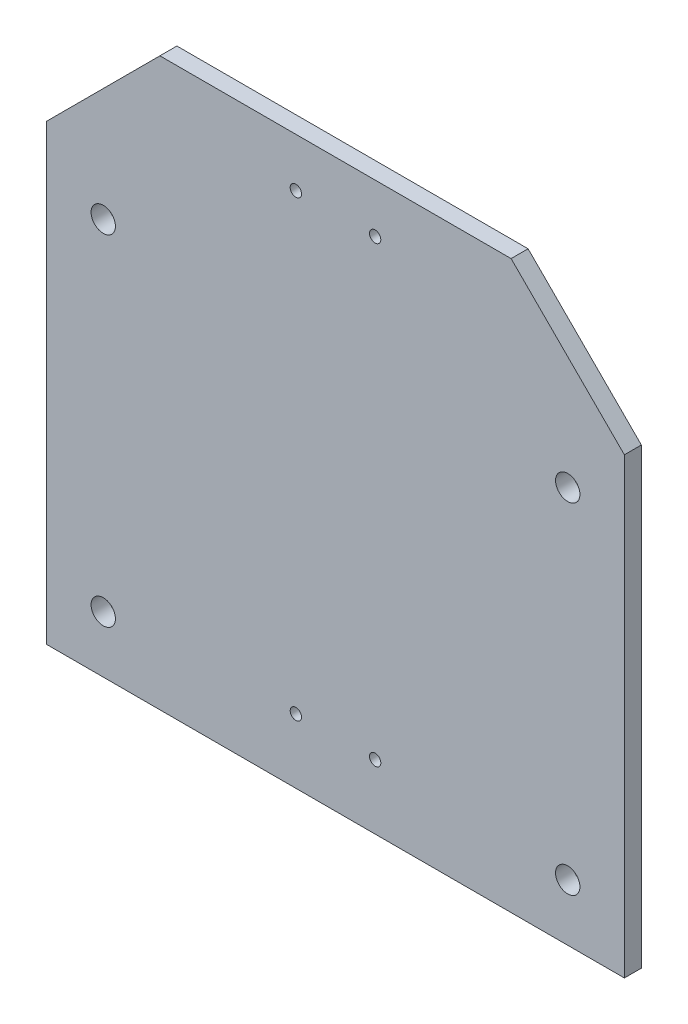
SolidWorks part; units mm, degrees
ref_plane "前视基准面" through (0, 0, 0) normal (0, 0, 1) x (1, 0, 0)
ref_plane "上视基准面" through (0, 0, 0) normal (0, 1, 0) x (1, 0, 0)
ref_plane "右视基准面" through (0, 0, 0) normal (1, 0, 0) x (0, 0, -1)
sketch "草图1" plane through (0, 0, 0) normal (0, 0, 1) x (1, 0, 0)
  line L0 (-51.0025, -60.1275) -> (51.0025, -60.1275)
  line L1 (-51.0025, -146.8866) -> (-51.0025, 19.8725) construction
  line L2 (51.0025, 19.8725) -> (51.0025, -146.8866) construction
  line L3 (51.0025, -60.1275) -> (51.0025, 19.8725)
  line L4 (51.0025, 19.8725) -> (31.0025, 39.8725) construction
  line L5 (51.0025, 19.8725) -> (31.0025, 39.8725)
  line L6 (31.0025, 39.8725) -> (-31.0025, 39.8725)
  line L7 (-31.0025, 39.8725) -> (-51.0025, 19.8725)
  line L8 (-51.0025, 19.8725) -> (-51.0025, -60.1275)
  dimension "D1" = 100
extrude "凸台-拉伸1" add sketch "草图1" against normal blind 3
sketch "草图2" plane through (0, 0, 0) normal (0, 0, 1) x (1, 0, 0)
  circle A0 centre (-41.0025, 9.8725) radius 2.15
  circle A1 centre (-41.0025, -50.1275) radius 2.15
  circle A2 centre (41.0025, 9.8725) radius 2.15
  circle A3 centre (41.0025, -50.1275) radius 2.15
extrude "切除-拉伸1" cut sketch "草图2" against normal blind 3
sketch "草图3" plane through (0, 0, -3) normal (0, 0, -1) x (-1, 0, 0)
  circle A0 centre (-7.0002, 31.25) radius 1
  circle A1 centre (6.9998, 31.25) radius 1
  circle A2 centre (-7.0002, -48.75) radius 1
  circle A3 centre (6.9998, -48.75) radius 1
extrude "切除-拉伸2" cut sketch "草图3" against normal blind 70
